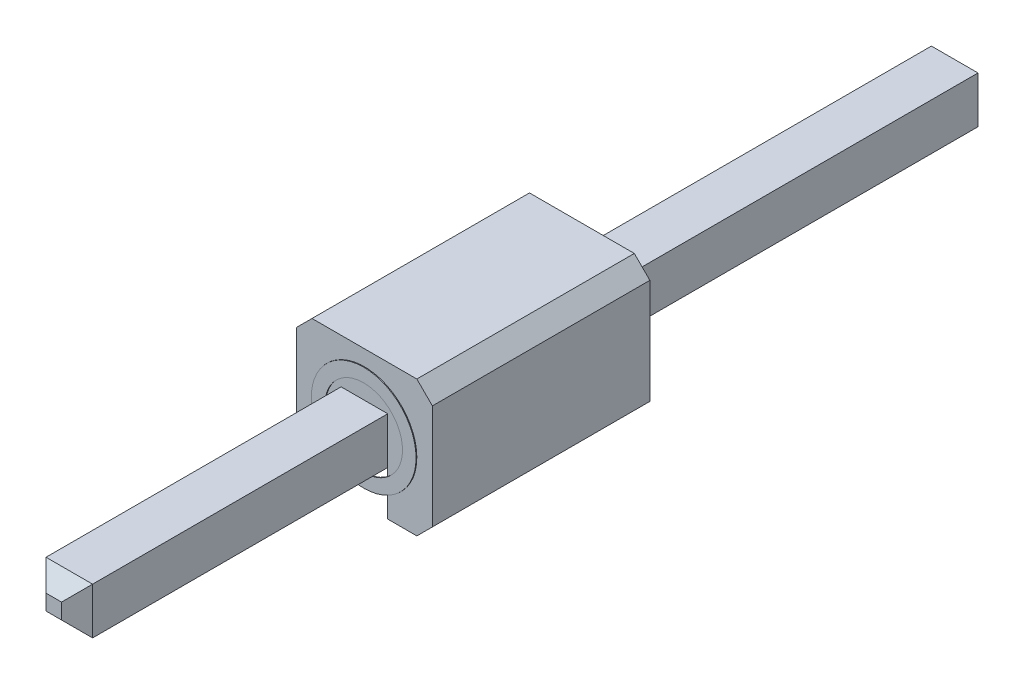
SolidWorks part; units mm, degrees
ref_plane "Plan de face" through (0, 0, 0) normal (0, 0, 1) x (1, 0, 0)
ref_plane "Plan de dessus" through (0, 0, 0) normal (0, 1, 0) x (1, 0, 0)
ref_plane "Plan de droite" through (0, 0, 0) normal (1, 0, 0) x (0, 0, -1)
sketch "Esquisse1" plane through (0, 0, 0) normal (0, 0, 1) x (1, 0, 0)
  line L0 (-0.675, 0.875) -> (-0.875, 0.675)
  line L1 (0.675, -0.875) -> (-0.675, -0.875)
  line L2 (0.875, -0.675) -> (0.875, 0.675)
  line L3 (0.675, 0.875) -> (-0.675, 0.875)
  line L4 (-0.875, -0.675) -> (-0.875, 0.675)
  line L5 (0.875, -0.875) -> (-0.875, 0.875) construction
  line L6 (0.875, 0.875) -> (-0.875, -0.875) construction
  line L7 (-0.675, -0.875) -> (-0.875, -0.675)
  line L8 (0.875, -0.675) -> (0.675, -0.875)
  line L9 (0.875, 0.675) -> (0.675, 0.875)
  line L11 (-0.3, 0.3) -> (0.3, 0.3)
  line L12 (-0.3, 0.3) -> (-0.3, -0.3)
  line L13 (-0.3, -0.3) -> (0.3, -0.3)
  line L14 (0.3, 0.3) -> (0.3, -0.3)
  line L15 (-0.3, 0.3) -> (0.3, -0.3) construction
  line L16 (-0.3, -0.3) -> (0.3, 0.3) construction
  point P0 (0, 0)
  point P14 (0, 0)
  dimension "D1" = 1.75
  dimension "D2" = 0.6
extrude "Boss.-Extru.1" add sketch "Esquisse1" along normal blind 2.8
sketch "Esquisse2" plane through (0, 0, 2.8) normal (0, 0, 1) x (1, 0, 0)
  line L0 (-0.3, -0.3) -> (0.3, -0.3) construction
  line L1 (-0.3, -0.3) -> (0.3, -0.3)
  line L2 (-0.675, -0.875) -> (0.675, -0.875) construction
  line L3 (-0.3, -0.875) -> (0.3, -0.875)
  line L4 (-0.3, -0.3) -> (-0.3, -0.875)
  line L5 (0.3, -0.3) -> (0.3, -0.875)
extrude "Enlèv. mat.-Extru.1" cut sketch "Esquisse2" against normal blind 1
sketch "Esquisse3" plane through (0, 0, 2.8) normal (0, 0, 1) x (1, 0, 0)
  line L0 (0.3, -0.3) -> (-0.3, -0.3) construction
  line L1 (-0.3, 0.3) -> (-0.3, -0.875) construction
  line L2 (0.3, 0.3) -> (-0.3, 0.3) construction
  line L3 (0.3, -0.875) -> (0.3, 0.3) construction
  line L4 (0.3, -0.3) -> (-0.3, -0.3)
  line L5 (-0.3, 0.3) -> (-0.3, -0.3)
  line L6 (0.3, 0.3) -> (-0.3, 0.3)
  line L7 (0.3, -0.3) -> (0.3, 0.3)
extrude "Boss.-Extru.2" add sketch "Esquisse3" along normal blind 4 and the other way blind 7.8
chamfer "Chanfrein1" distance 0.2 angle 45 8 edges at (0, 0.3, -5) (-0.3, 0, -5) (0, -0.3, -5) (0.3, 0, -5) (0, -0.3, 6.8) (-0.3, 0, 6.8) (0, 0.3, 6.8) (0.3, 0, 6.8)
sketch "Esquisse4" plane through (0, 0, 2.8) normal (0, 0, 1) x (1, 0, 0)
  circle A0 centre (0, 0) radius 0.5
  circle A1 centre (0, 0) radius 0.6746
  dimension "D1" = 1
extrude "Boss.-Extru.3" add sketch "Esquisse4" along normal blind 0.01
